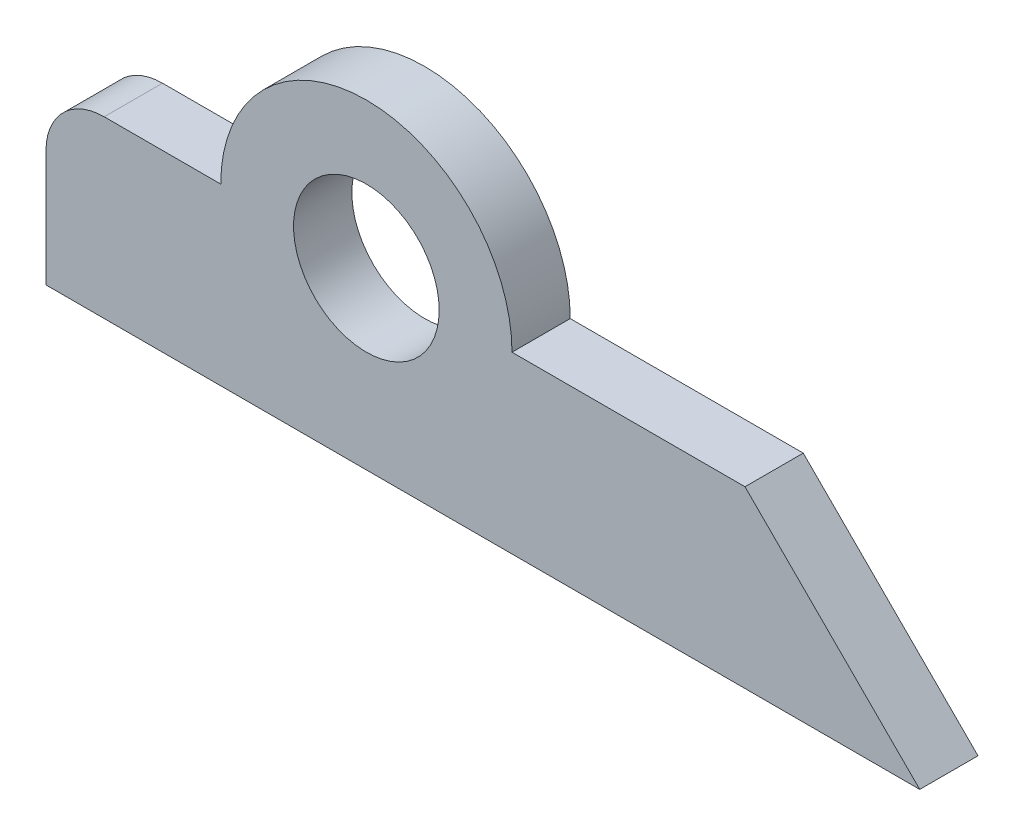
SolidWorks part; units mm, degrees
ref_plane "Front Plane" through (0, 0, 0) normal (0, 0, 1) x (1, 0, 0)
ref_plane "Top Plane" through (0, 0, 0) normal (0, 1, 0) x (1, 0, 0)
ref_plane "Right Plane" through (0, 0, 0) normal (1, 0, 0) x (0, 0, -1)
sketch "Sketch1" plane through (0, 0, 0) normal (0, 0, 1) x (1, 0, 0)
  line L0 (-25, 0) -> (-45, 0)
  line L1 (-55, -10) -> (-55, -30)
  line L2 (-55, -30) -> (95, -30)
  line L5 (25, 0) -> (65, 0)
  line L6 (65, 0) -> (95, -30)
  circle A0 centre (0, 0) radius 12.5
  arc A2 (25, 0) -> (-25, 0) centre (0, 0) ccw
  arc A3 (-45, 0) -> (-55, -10) centre (-45, -10) ccw
  point P10 (0, 25)
  point P13 (-55, 0)
  dimension "D3" = 55
  dimension "D4" = 25
  dimension "D5" = 25
  dimension "D7" = 10
  dimension "D1" = 150
  dimension "D2" = 30
  dimension "D6" = 45
extrude "Boss-Extrude1" add sketch "Sketch1" along normal blind 10
